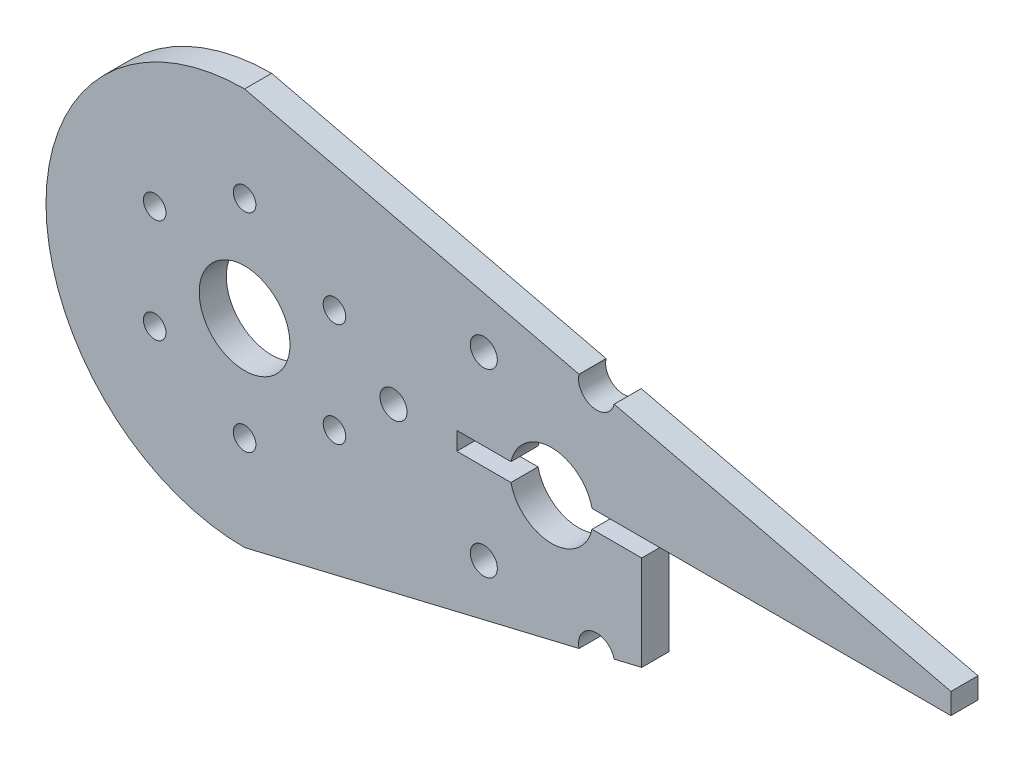
SolidWorks part; units mm, degrees
ref_plane "前视基准面" through (0, 0, 0) normal (0, 0, 1) x (1, 0, 0)
ref_plane "上视基准面" through (0, 0, 0) normal (0, 1, 0) x (1, 0, 0)
ref_plane "右视基准面" through (0, 0, 0) normal (1, 0, 0) x (0, 0, -1)
sketch "草图1" plane through (0, 0, 0) normal (0, 0, 1) x (1, 0, 0)
  line L0 (-38.999, 0) -> (5.001, 0) construction
  line L1 (-38.999, 22.002) -> (5.001, 22.002) construction
  line L6 (-38.999, 22.002) -> (-38.999, -22.002) construction
  line L7 (-38.999, -22.002) -> (5.001, -22.002) construction
  line L11 (5.001, 22.002) -> (5.001, -22.002) construction
  line L12 (5.001, 22.002) -> (5.001, 1) construction
  line L13 (-15.489, 1) -> (-9.489, 1)
  line L31 (-15.489, 1) -> (-15.489, -1)
  line L35 (-15.489, -1) -> (-9.489, -1)
  line L36 (-9.489, 1) -> (-9.489, -1) construction
  line L37 (5.001, 1) -> (-0.509, 1)
  line L39 (5.001, -1) -> (-0.509, -1)
  line L40 (-0.509, 1) -> (-0.509, -1) construction
  line L41 (5.001, -1) -> (5.001, -22.002) construction
  line L42 (5.001, 11.501) -> (-38.999, 22.002)
  line L43 (5.001, -11.501) -> (-38.999, -22.002)
  line L44 (5.001, 11.501) -> (5.001, 1) construction
  line L45 (5.001, -1) -> (5.001, -11.501)
  line L46 (5.001, 1) -> (39.2548, 1)
  line L47 (5.001, 11.501) -> (39.2548, 3.326)
  line L48 (39.2548, 3.326) -> (39.2548, 1)
  circle A3 centre (-38.999, 0) radius 5.03
  circle A6 centre (-38.999, 0) radius 11.5 construction
  circle A7 centre (-38.999, -11.5) radius 1.25
  circle A18 centre (-38.999, 0) radius 22.002 construction
  arc A35 (-38.999, 22.002) -> (-38.999, -22.002) centre (-38.999, 0) ccw
  circle A37 centre (-4.999, 0) radius 4.6 construction
  arc A38 (-0.509, 1) -> (-9.489, 1) centre (-4.999, 0) ccw
  arc A39 (-0.509, -1) -> (-9.489, -1) centre (-4.999, 0) cw
  circle A43 centre (-12.499, -10) radius 1.5
  circle A45 centre (-38.999, 0) radius 16.5 construction
  circle A46 centre (-22.499, 0) radius 1.5
  circle A47 centre (-48.9583, -5.75) radius 1.25
  circle A48 centre (-12.499, 10) radius 1.5
  circle A49 centre (-48.9583, 5.75) radius 1.25
  circle A50 centre (-38.999, 11.5) radius 1.25
  circle A51 centre (-29.0397, 5.75) radius 1.25
  circle A52 centre (-29.0397, -5.75) radius 1.25
  point P45 (-61.001, 0)
  dimension "D3" = 10.06
  dimension "D4" = 44
  dimension "D5" = 9.2
  dimension "D6" = 10
  dimension "D7" = 23
  dimension "D8" = 2.5
  dimension "D9" = 2
  dimension "D11" = 33
  dimension "D14" = 10
  dimension "D2" = 44.004
  dimension "D15" = 10
  dimension "D10" = 6
  dimension "D16" = 6
extrude "凸台-拉伸1" add sketch "草图1" along normal blind 3
sketch "草图2" plane through (0, 0, 0) normal (0, 0, -1) x (-1, 0, 0)
  line L0 (-39.2548, 3.326) -> (38.999, 22.002) construction
  line L1 (38.999, -22.002) -> (-5.001, -11.501) construction
  line L2 (15.489, 1) -> (9.489, 1) construction
  line L3 (4.1121, 14.14) -> (22.3299, 14.14) construction
  line L4 (4.1121, 14.14) -> (4.1121, 28.2304) construction
  line L5 (4.1121, 28.2304) -> (22.3299, 28.2304) construction
  line L6 (22.3299, 14.14) -> (22.3299, 28.2304) construction
  line L7 (22.499, 0) -> (4.7868, 0) construction
  circle A0 centre (0, 12.6945) radius 2
  circle A1 centre (0, -12.6945) radius 2
  dimension "D1" = 13.14
extrude "切除-拉伸1" cut sketch "草图2" against normal blind 4
